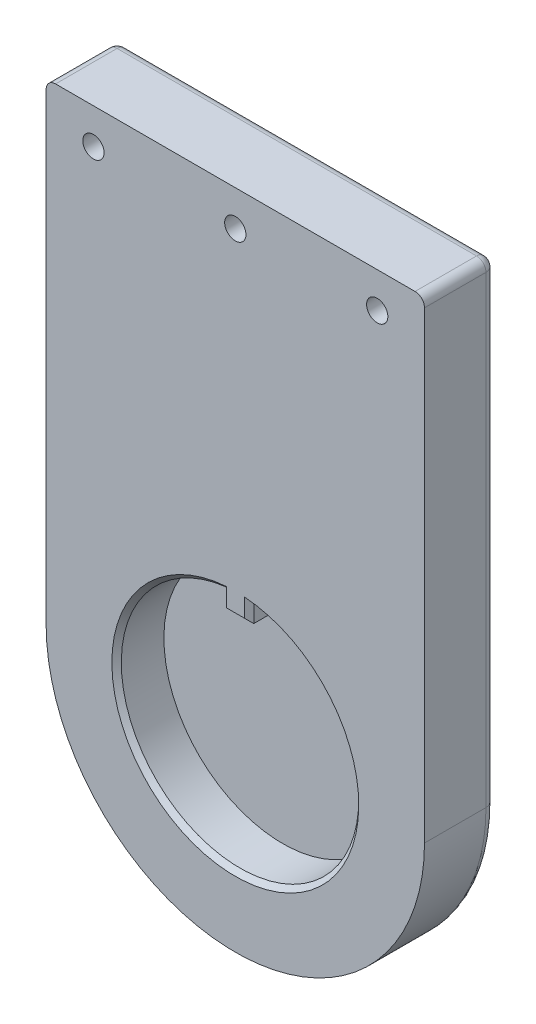
SolidWorks part; units mm, degrees
ref_plane "Front Plane" through (0, 0, 0) normal (0, 0, 1) x (1, 0, 0)
ref_plane "Top Plane" through (0, 0, 0) normal (0, 1, 0) x (1, 0, 0)
ref_plane "Right Plane" through (0, 0, 0) normal (1, 0, 0) x (0, 0, -1)
sketch "Sketch1" plane through (0, 0, 0) normal (0, 0, 1) x (1, 0, 0)
  circle A0 centre (0, 0) radius 40
  dimension "D1" = 80
extrude "Boss-Extrude1" add sketch "Sketch1" along normal blind 15
sketch "Sketch2" plane through (0, 0, 15) normal (0, 0, 1) x (1, 0, 0)
  line L0 (0, 0) -> (0, 40) construction
  circle A0 centre (0, 0) radius 40 construction
  circle A1 centre (0, 0) radius 25.1
  dimension "D1" = 50.2
extrude "Cut-Extrude1" cut sketch "Sketch2" against normal blind 10
sketch "Sketch3" plane through (0, 0, 15) normal (0, 0, 1) x (1, 0, 0)
  line L0 (0, 0) -> (0, 41.4765) construction
  line L1 (2.9, 21.1319) -> (-2.9, 21.1319)
  line L2 (-2.9, 21.1319) -> (-2.9, 24.9319)
  line L3 (2.9, 21.1319) -> (2.9, 24.9319)
  circle A0 centre (0, 0) radius 25.1 construction
  arc A1 (2.9, 24.9319) -> (-2.9, 24.9319) centre (0, 0) ccw
  point P11 (0, 21.1319)
  dimension "D1" = 5.8
  dimension "D2" = 3.8
extrude "Boss-Extrude2" add sketch "Sketch3" against normal blind 10
chamfer "Chamfer1" distance 1 angle 45 4 edges at (2.9, 23.0319, 15) (0, 21.1319, 15) (-2.9, 23.0319, 15) (0, -25.1, 15)
sketch "Sketch4" plane through (0, 0, 0) normal (0, 0, -1) x (-1, 0, 0)
  line L0 (0, 0) -> (0, 178.7895) construction
  line L1 (-40, 0) -> (-40, 100)
  line L2 (-40, 100) -> (40, 100)
  line L3 (40, 0) -> (40, 100)
  circle A0 centre (0, 0) radius 40 construction
  arc A2 (40, 0) -> (-40, 0) centre (0, 0) ccw
  point P9 (0, 100)
  dimension "D1" = 80
  dimension "D2" = 100
extrude "Boss-Extrude3" add sketch "Sketch4" against normal through all
sketch "Sketch5" plane through (0, 0, 0) normal (0, 0, -1) x (-1, 0, 0)
  line L0 (-40, 92.5) -> (40, 92.5) construction
  line L1 (-40, 100) -> (-40, 0) construction
  line L2 (40, 0) -> (40, 100) construction
  line L3 (40, 100) -> (-40, 100) construction
  line L4 (0, 100) -> (0, 128.5516) construction
  circle A0 centre (0, 92.5) radius 2.25
  circle A1 centre (-30, 92.5) radius 2.25
  circle A2 centre (30, 92.5) radius 2.25
  dimension "D3" = 4.5
  dimension "D4" = 4.5
  dimension "D1" = 7.5
  dimension "D2" = 60
extrude "Cut-Extrude2" cut sketch "Sketch5" against normal through all
fillet "Fillet1" radius 2 6 edges at (40, 50, 0) (0, -40, 0) (40, 100, 7.5) (-40, 100, 7.5) (-40, 50, 0) (0, 100, 0)
